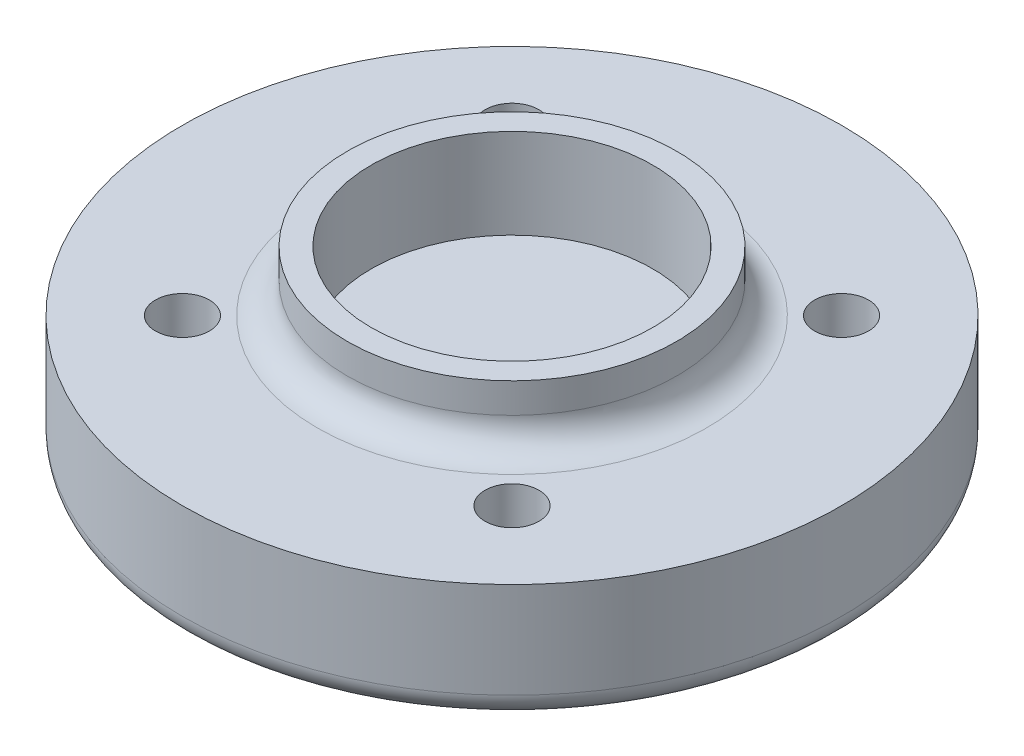
SolidWorks part; units mm, degrees
ref_plane "Front Plane" through (0, 0, 0) normal (0, 0, 1) x (1, 0, 0)
ref_plane "Top Plane" through (0, 0, 0) normal (0, 1, 0) x (1, 0, 0)
ref_plane "Right Plane" through (0, 0, 0) normal (1, 0, 0) x (0, 0, -1)
sketch "Sketch1" plane through (0, 0, 0) normal (0, 1, 0) x (1, 0, 0)
  circle A0 centre (0, 0) radius 55
  dimension "D1" = 110
extrude "Boss-Extrude1" add sketch "Sketch1" along normal blind 20
sketch "Sketch2" plane through (0, 20, 0) normal (0, 1, 0) x (1, 0, 0)
  circle A0 centre (0, 0) radius 27.5
  dimension "D1" = 55
extrude "Boss-Extrude2" add sketch "Sketch2" along normal blind 10
sketch "Sketch6" plane through (0, 30, 0) normal (0, 1, 0) x (1, 0, 0)
  circle A2 centre (0, 0) radius 23.5
  circle A3 centre (0, 0) radius 23.5
  dimension "D1" = 4
extrude "Cut-Extrude1" cut sketch "Sketch6" against normal blind 15
fillet "Fillet1" radius 5 1 edges at (0, 20, 27.5)
sketch "Sketch7" plane through (0, 0, 0) normal (0, -1, 0) x (1, 0, 0)
  line L1 (-27.5, 27.5) -> (27.5, 27.5) construction
  line L2 (-27.5, 27.5) -> (-27.5, -27.5) construction
  line L3 (-27.5, -27.5) -> (27.5, -27.5) construction
  line L4 (27.5, 27.5) -> (27.5, -27.5) construction
  line L5 (-27.5, 27.5) -> (27.5, -27.5) construction
  line L6 (-27.5, -27.5) -> (27.5, 27.5) construction
  point P0 (0, 0)
  dimension "D1" = 55
  dimension "D2" = 55
hole_wizard "CBORE for M8 Hex Head Bolt1" positions "3DSketch1" profile "Sketch8" counterbore size "M8" standard "ISO" end condition through all
sketch3d "3DSketch1"
  point P0 (27.5, 0, -27.5)
  point P3 (-27.5, 0, -27.5)
  point P6 (-27.5, 0, 27.5)
  point P9 (27.5, 0, 27.5)
sketch "Sketch8" plane through (27.5, 0, -27.5) normal (1, 0, 0) x (0, 0, -1)
  line L0 (0, 0) -> (0, 30)
  line L1 (0, 30) -> (4.5, 30)
  line L3 (4.5, 30) -> (4.5, 5.3)
  line L4 (4.5, 5.3) -> (9.0055, 5.3)
  line L5 (9.0055, 5.3) -> (9.0055, 0)
  line L7 (9.0055, 0) -> (0, 0)
  line L11 (0, -6.35) -> (0, 107.95) construction
  dimension "Thru Hole Dia." = 9
  dimension "Thru Hole Depth" = 30
  dimension "C'Bore Dia." = 18.011
  dimension "C'Bore Depth" = 5.3
fillet "Fillet2" radius 4 1 edges at (0, 0, 55)
